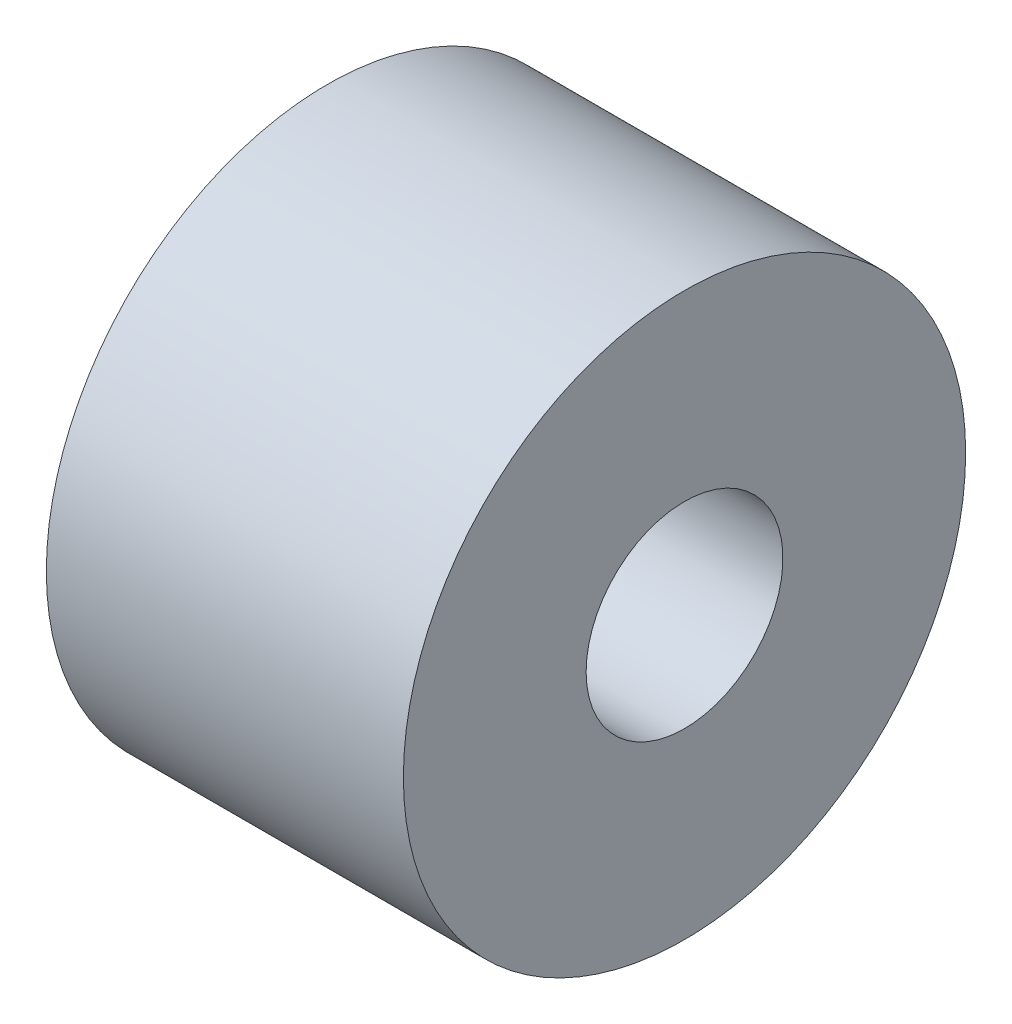
SolidWorks part; units mm, degrees
ref_plane "Front Plane" through (0, 0, 0) normal (0, 0, 1) x (1, 0, 0)
ref_plane "Top Plane" through (0, 0, 0) normal (0, 1, 0) x (1, 0, 0)
ref_plane "Right Plane" through (0, 0, 0) normal (1, 0, 0) x (0, 0, -1)
other "Bounding Box"
ref_plane "Default Plane" through (0, -11.5846, 8.1116) normal (0, 0.9848, 0.1736) x (1, 0, 0)
sketch "Sketch1" plane through (0, 0, 0) normal (1, 0, 0) x (0, 0, -1)
  circle A0 centre (0, 0) radius 10
extrude "Boss-Extrude1" add sketch "Sketch1" along normal blind 12.7 contours A0
sketch "Sketch2" plane through (0, 0, 0) normal (-1, 0, 0) x (0, 0, 1)
  circle A0 centre (0, 0) radius 3.5
extrude "Cut-Extrude1" cut sketch "Sketch2" against normal blind 12.7
